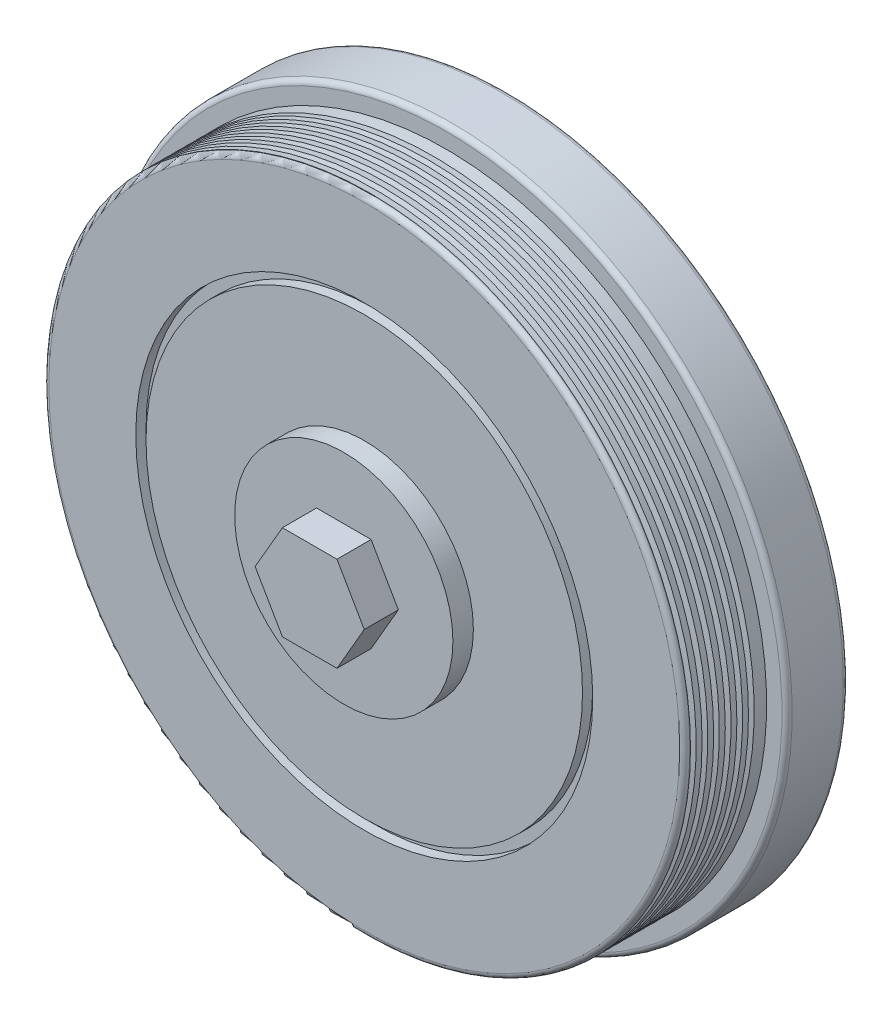
SolidWorks part; units mm, degrees
ref_plane "Front Plane" through (0, 0, 0) normal (0, 0, 1) x (1, 0, 0)
ref_plane "Top Plane" through (0, 0, 0) normal (0, 1, 0) x (1, 0, 0)
ref_plane "Right Plane" through (0, 0, 0) normal (1, 0, 0) x (0, 0, -1)
other "Configuration Table"
sketch "Sketch1" plane through (0, 0, 0) normal (1, 0, 0) x (0, 0, -1)
  line L0 (-80, 0) -> (-90, 0) construction
  line L1 (-98, 25.05) -> (-98, 98.5)
  line L2 (-99.5, 100) -> (-114.5, 100)
  line L3 (-116, 98.5) -> (-116, 94)
  line L4 (-116, 94) -> (-138.5, 94)
  line L5 (-140, 92.5) -> (-140, 25.05)
  line L6 (-140, 25.05) -> (-98, 25.05)
  arc A0 (-98, 98.5) -> (-99.5, 100) centre (-99.5, 98.5) ccw
  arc A1 (-114.5, 100) -> (-116, 98.5) centre (-114.5, 98.5) ccw
  arc A2 (-138.5, 94) -> (-140, 92.5) centre (-138.5, 92.5) ccw
revolve "Balancer" add sketch "Sketch1" angle 360 about L0
sketch "Sketch2" plane through (0, 0, 0) normal (1, 0, 0) x (0, 0, -1)
  line L0 (-80, 0) -> (-90, 0) construction
  line L1 (-119, 96) -> (-120.5, 91.5)
  line L2 (-120.5, 91.5) -> (-122, 96)
  line L3 (-122, 96) -> (-119, 96)
  line L4 (-122.4, 96) -> (-123.9, 91.5)
  line L5 (-123.9, 91.5) -> (-125.4, 96)
  line L6 (-125.4, 96) -> (-122.4, 96)
  line L7 (-125.8, 96) -> (-127.3, 91.5)
  line L8 (-127.3, 91.5) -> (-128.8, 96)
  line L9 (-128.8, 96) -> (-125.8, 96)
  line L10 (-129.2, 96) -> (-130.7, 91.5)
  line L11 (-130.7, 91.5) -> (-132.2, 96)
  line L12 (-132.2, 96) -> (-129.2, 96)
  line L13 (-132.6, 96) -> (-134.1, 91.5)
  line L14 (-134.1, 91.5) -> (-135.6, 96)
  line L15 (-135.6, 96) -> (-132.6, 96)
  line L16 (-136, 96) -> (-137.5, 91.5)
  line L17 (-137.5, 91.5) -> (-139, 96)
  line L18 (-139, 96) -> (-136, 96)
revolve "Belt Grooves" cut sketch "Sketch2" angle 360 about L0
sketch "Sketch3" plane through (0, 0, 0) normal (1, 0, 0) x (0, 0, -1)
  line L0 (-80, 0) -> (-90, 0) construction
  line L1 (-137, 64) -> (-137, 67)
  line L2 (-137, 67) -> (-141, 67)
  line L3 (-141, 67) -> (-141, 64)
  line L4 (-141, 64) -> (-137, 64)
revolve "Isolator Groove" cut sketch "Sketch3" angle 360 about L0
sketch "Sketch4" plane through (0, 0, 0) normal (0, 0, 1) x (1, 0, 0)
  circle A0 centre (0, 0) radius 32
extrude "Washer" add sketch "Sketch4" along normal blind 6 from offset 140
sketch "Sketch5" plane through (0, 0, 0) normal (0, 0, 1) x (1, 0, 0)
  line L0 (16, 0) -> (8, 13.8564)
  line L1 (8, 13.8564) -> (-8, 13.8564)
  line L2 (-8, 13.8564) -> (-16, 0)
  line L3 (-16, 0) -> (-8, -13.8564)
  line L4 (-8, -13.8564) -> (8, -13.8564)
  line L5 (8, -13.8564) -> (16, 0)
extrude "Crank Bolt" add sketch "Sketch5" along normal blind 10 from offset 146
